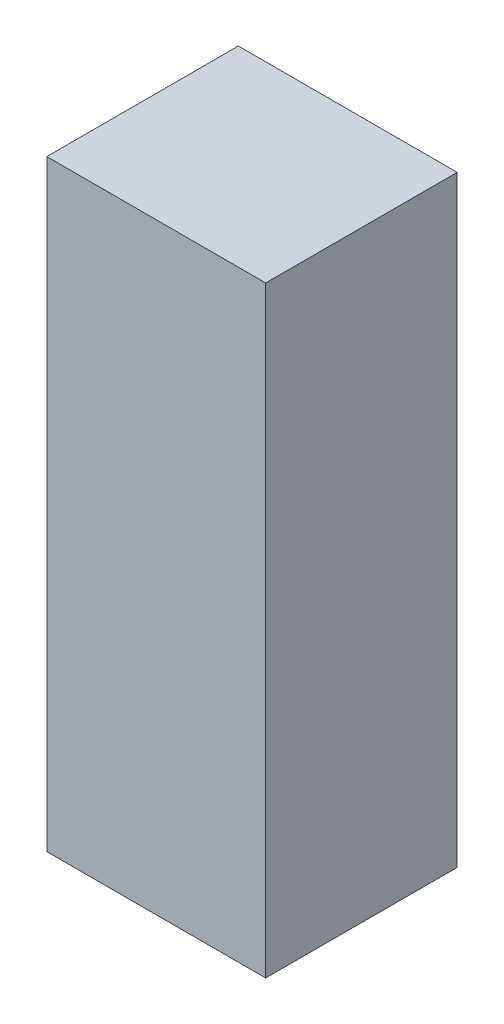
SolidWorks part; units mm, degrees
ref_plane "前视基准面" through (0, 0, 0) normal (0, 0, 1) x (1, 0, 0)
ref_plane "上视基准面" through (0, 0, 0) normal (0, 1, 0) x (1, 0, 0)
ref_plane "右视基准面" through (0, 0, 0) normal (1, 0, 0) x (0, 0, -1)
sketch "草图1" plane through (0, 0, 0) normal (0, 1, 0) x (1, 0, 0)
  line L1 (-20, -17.5) -> (20, -17.5)
  line L2 (-20, -17.5) -> (-20, 17.5)
  line L3 (-20, 17.5) -> (20, 17.5)
  line L4 (20, -17.5) -> (20, 17.5)
  line L5 (-20, -17.5) -> (20, 17.5) construction
  line L6 (-20, 17.5) -> (20, -17.5) construction
  point P0 (0, 0)
  dimension "D1" = 40
  dimension "D2" = 35
extrude "凸台-拉伸1" add sketch "草图1" along normal blind 110
